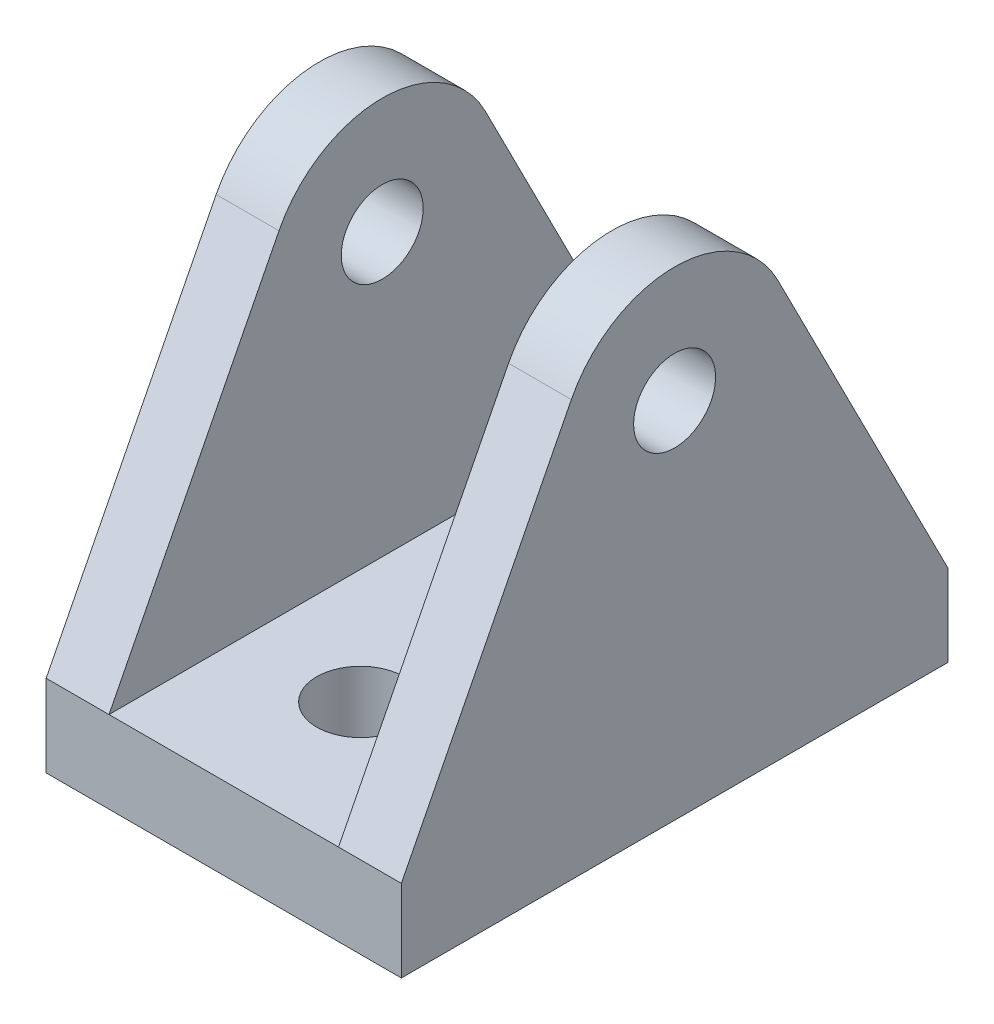
SolidWorks part; units mm, degrees
ref_plane "前视基准面" through (0, 0, 0) normal (0, 0, 1) x (1, 0, 0)
ref_plane "上视基准面" through (0, 0, 0) normal (0, 1, 0) x (1, 0, 0)
ref_plane "右视基准面" through (0, 0, 0) normal (1, 0, 0) x (0, 0, -1)
other "Configuration Table"
sketch "草图1" plane through (0, 0, 0) normal (0, 1, 0) x (1, 0, 0)
  line L0 (0, 10) -> (0, 0) construction
  line L1 (-6.5, 10) -> (6.5, 10)
  line L2 (-6.5, 10) -> (-6.5, -10)
  line L3 (-6.5, -10) -> (6.5, -10)
  line L4 (6.5, 10) -> (6.5, -10)
  line L5 (0, 0) -> (6.5, 0) construction
  circle A0 centre (0, 5) radius 1.6
  circle A1 centre (0, -5) radius 1.6
  dimension "D3" = 3.2
  dimension "D1" = 13
  dimension "D2" = 20
extrude "凸台-拉伸1" add sketch "草图1" along normal blind 3
sketch "草图2" plane through (-6.5, 0, 0) normal (-1, 0, 0) x (0, 0, 1)
  line L0 (0, 0) -> (0, 13.3) construction
  line L1 (-10, 3) -> (10, 3)
  line L2 (-10, 3) -> (10, 3) construction
  line L3 (-10, 3) -> (-3.7787, 15.2233)
  line L4 (10, 3) -> (3.7787, 15.2233)
  line L5 (-10, 0) -> (10, 0) construction
  circle A0 centre (0, 13.3) radius 1.5
  arc A1 (-3.7787, 15.2233) -> (3.7787, 15.2233) centre (0, 13.3) cw
  point P15 (0, 3)
  dimension "D1" = 3
  dimension "D2" = 4.24
  dimension "D3" = 13.3
extrude "凸台-拉伸2" add sketch "草图2" against normal up to surface (13 mm away) up to face at (6.5, 1.5, 0)
sketch "草图3" plane through (0, 0, -10) normal (0, 0, -1) x (-1, 0, 0)
  line L0 (-6.5, 3) -> (6.5, 3) construction
  line L1 (-4.2, 3) -> (4.2, 3)
  line L2 (-4.2, 3) -> (-4.2, 17.54)
  line L3 (-4.2, 17.54) -> (4.2, 17.54)
  line L4 (4.2, 3) -> (4.2, 17.54)
  line L5 (6.5, 17.54) -> (-6.5, 17.54) construction
  line L6 (0, 0) -> (0, 3) construction
  dimension "D1" = 8.4
extrude "切除-拉伸1" cut sketch "草图3" against normal through all
